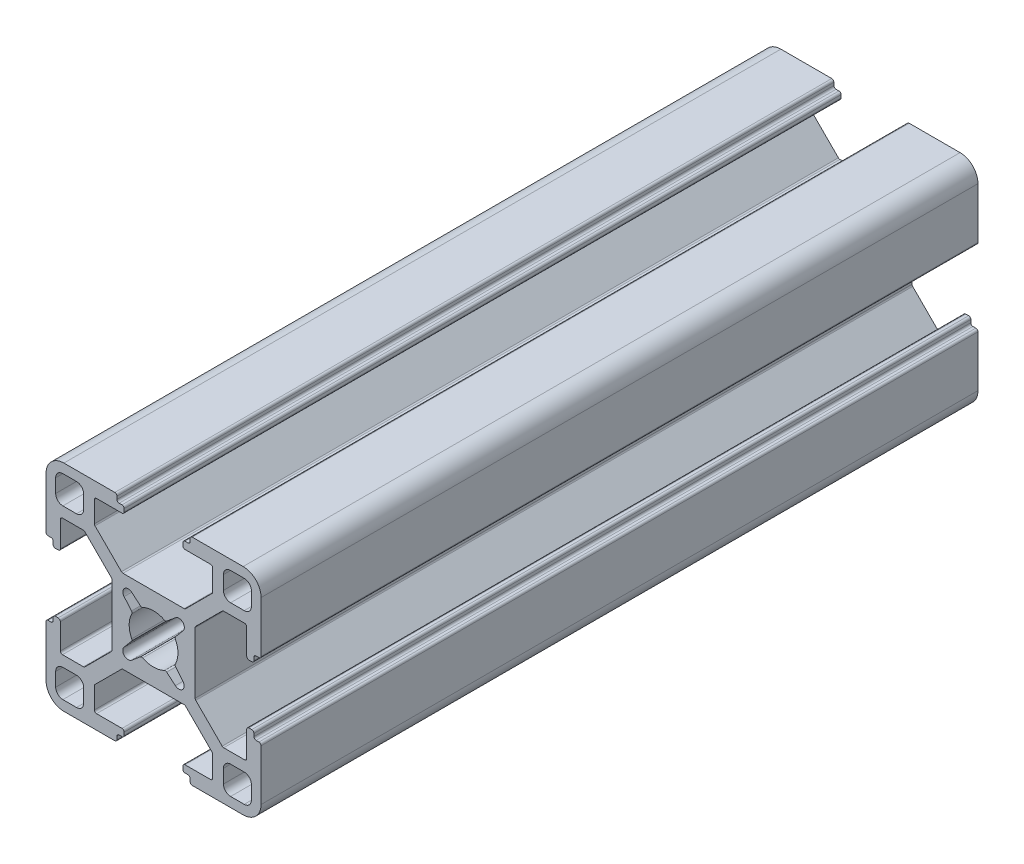
SolidWorks part; units mm, degrees
ref_plane "前视基准面" through (0, 0, 0) normal (0, 0, 1) x (1, 0, 0)
ref_plane "上视基准面" through (0, 0, 0) normal (0, 1, 0) x (1, 0, 0)
ref_plane "右视基准面" through (0, 0, 0) normal (1, 0, 0) x (0, 0, -1)
sketch "草图1" plane through (0, 0, 0) normal (0, 0, 1) x (1, 0, 0)
  line B0 (-13.65, 12.65) -> (-13.65, 10.75)
  line B1 (-12.65, 9.75) -> (-10.75, 9.75)
  line B2 (-9.75, 10.75) -> (-9.75, 12.65)
  line B3 (-10.75, 13.65) -> (-12.65, 13.65)
  line B4 (12.65, 13.65) -> (10.75, 13.65)
  line B5 (9.75, 12.65) -> (9.75, 10.75)
  line B6 (10.75, 9.75) -> (12.65, 9.75)
  line B7 (13.65, 10.75) -> (13.65, 12.65)
  line B8 (-12.65, -13.65) -> (-10.75, -13.65)
  line B9 (-9.75, -12.65) -> (-9.75, -10.75)
  line B10 (-10.75, -9.75) -> (-12.65, -9.75)
  line B11 (-13.65, -10.75) -> (-13.65, -12.65)
  line B12 (9.75, -10.75) -> (9.75, -12.65)
  line B13 (10.75, -13.65) -> (12.65, -13.65)
  line B14 (13.65, -12.65) -> (13.65, -10.75)
  line B15 (12.65, -9.75) -> (10.75, -9.75)
  line B16 (14.3, 5.1) -> (14.7, 5.1)
  line B17 (15, 5.4) -> (15, 12.5)
  line B18 (12.5, 15) -> (5.4, 15)
  line B19 (5.1, 14.7) -> (5.1, 14.3)
  line B20 (4.8, 14) -> (4.4, 14)
  line B21 (4.1, 13.7) -> (4.1, 13.3)
  line B22 (4.4, 13) -> (7.95, 13)
  line B23 (8.25, 12.7) -> (8.25, 9.7885)
  line B24 (8.1621, 9.5763) -> (4.4737, 5.8879)
  line B25 (4.2615, 5.8) -> (0, 5.8)
  line B26 (0, 5.8) -> (-4.2615, 5.8)
  line B27 (-4.4737, 5.8879) -> (-8.1621, 9.5763)
  line B28 (-8.25, 9.7885) -> (-8.25, 12.7)
  line B29 (-7.95, 13) -> (-4.4, 13)
  line B30 (-4.1, 13.3) -> (-4.1, 13.7)
  line B31 (-4.4, 14) -> (-4.8, 14)
  line B32 (-5.1, 14.3) -> (-5.1, 14.7)
  line B33 (-5.4, 15) -> (-12.5, 15)
  line B34 (-15, 12.5) -> (-15, 5.4)
  line B35 (-14.7, 5.1) -> (-14.3, 5.1)
  line B36 (-14, 4.8) -> (-14, 4.4)
  line B37 (-13.7, 4.1) -> (-13.3, 4.1)
  line B38 (-13, 4.4) -> (-13, 7.95)
  line B39 (-12.7, 8.25) -> (-9.7885, 8.25)
  line B40 (-9.5763, 8.1621) -> (-5.8879, 4.4737)
  line B41 (-5.8, 4.2615) -> (-5.8, 0)
  line B42 (-5.8, 0) -> (-5.8, -4.2615)
  line B43 (-5.8879, -4.4737) -> (-9.5763, -8.1621)
  line B44 (-9.7885, -8.25) -> (-12.7, -8.25)
  line B45 (-13, -7.95) -> (-13, -4.4)
  line B46 (-13.3, -4.1) -> (-13.7, -4.1)
  line B47 (-14, -4.4) -> (-14, -4.8)
  line B48 (-14.3, -5.1) -> (-14.7, -5.1)
  line B49 (-15, -5.4) -> (-15, -12.5)
  line B50 (-12.5, -15) -> (-5.4, -15)
  line B51 (-5.1, -14.7) -> (-5.1, -14.3)
  line B52 (-4.8, -14) -> (-4.4, -14)
  line B53 (-4.1, -13.7) -> (-4.1, -13.3)
  line B54 (-4.4, -13) -> (-7.95, -13)
  line B55 (-8.25, -12.7) -> (-8.25, -9.6642)
  line B56 (-8.25, -9.6642) -> (-4.3858, -5.8)
  line B57 (-4.3858, -5.8) -> (0, -5.8)
  line B58 (0, -5.8) -> (4.3858, -5.8)
  line B59 (4.3858, -5.8) -> (8.1621, -9.5763)
  line B60 (8.25, -9.7885) -> (8.25, -12.7)
  line B61 (7.95, -13) -> (4.4, -13)
  line B62 (4.1, -13.3) -> (4.1, -13.7)
  line B63 (4.4, -14) -> (4.8, -14)
  line B64 (5.1, -14.3) -> (5.1, -14.7)
  line B65 (5.4, -15) -> (12.5, -15)
  line B66 (15, -12.5) -> (15, -5.4)
  line B67 (14.7, -5.1) -> (14.3, -5.1)
  line B68 (14, -4.8) -> (14, -4.4)
  line B69 (13.7, -4.1) -> (13.3, -4.1)
  line B70 (13, -4.4) -> (13, -7.95)
  line B71 (12.7, -8.25) -> (9.7885, -8.25)
  line B72 (9.5763, -8.1621) -> (5.8879, -4.4737)
  line B73 (5.8, -4.2615) -> (5.8, 0)
  line B74 (5.8, 0) -> (5.8, 4.2615)
  line B75 (5.8879, 4.4737) -> (9.5763, 8.1621)
  line B76 (9.7885, 8.25) -> (12.7, 8.25)
  line B77 (13, 7.95) -> (13, 4.4)
  line B78 (13.3, 4.1) -> (13.7, 4.1)
  line B79 (14, 4.4) -> (14, 4.8)
  line B80 (-1.83, 3.0889) -> (-3.0493, 4.1167)
  line B81 (-4.103, 3.0678) -> (-3.0807, 1.8439)
  line B82 (-3.0889, -1.83) -> (-4.1167, -3.0493)
  line B83 (-3.0678, -4.103) -> (-1.8439, -3.0807)
  line B84 (1.83, -3.0889) -> (3.0493, -4.1167)
  line B85 (4.103, -3.0678) -> (3.0807, -1.8439)
  line B86 (3.0889, 1.83) -> (4.1167, 3.0493)
  line B87 (3.0678, 4.103) -> (1.8439, 3.0807)
  arc B88 (-13.65, 10.75) -> (-12.65, 9.75) centre (-12.65, 10.75) ccw
  arc B89 (-10.75, 9.75) -> (-9.75, 10.75) centre (-10.75, 10.75) ccw
  arc B90 (-9.75, 12.65) -> (-10.75, 13.65) centre (-10.75, 12.65) ccw
  arc B91 (-12.65, 13.65) -> (-13.65, 12.65) centre (-12.65, 12.65) ccw
  arc B92 (10.75, 13.65) -> (9.75, 12.65) centre (10.75, 12.65) ccw
  arc B93 (9.75, 10.75) -> (10.75, 9.75) centre (10.75, 10.75) ccw
  arc B94 (12.65, 9.75) -> (13.65, 10.75) centre (12.65, 10.75) ccw
  arc B95 (13.65, 12.65) -> (12.65, 13.65) centre (12.65, 12.65) ccw
  arc B96 (-13.65, -12.65) -> (-12.65, -13.65) centre (-12.65, -12.65) ccw
  arc B97 (-10.75, -13.65) -> (-9.75, -12.65) centre (-10.75, -12.65) ccw
  arc B98 (-9.75, -10.75) -> (-10.75, -9.75) centre (-10.75, -10.75) ccw
  arc B99 (-12.65, -9.75) -> (-13.65, -10.75) centre (-12.65, -10.75) ccw
  arc B100 (10.75, -9.75) -> (9.75, -10.75) centre (10.75, -10.75) ccw
  arc B101 (9.75, -12.65) -> (10.75, -13.65) centre (10.75, -12.65) ccw
  arc B102 (12.65, -13.65) -> (13.65, -12.65) centre (12.65, -12.65) ccw
  arc B103 (13.65, -10.75) -> (12.65, -9.75) centre (12.65, -10.75) ccw
  arc B104 (14.7, 5.1) -> (15, 5.4) centre (14.7, 5.4) ccw
  arc B105 (15, 12.5) -> (12.5, 15) centre (12.5, 12.5) ccw
  arc B106 (5.4, 15) -> (5.1, 14.7) centre (5.4, 14.7) ccw
  arc B107 (4.8, 14) -> (5.1, 14.3) centre (4.8, 14.3) ccw
  arc B108 (4.4, 14) -> (4.1, 13.7) centre (4.4, 13.7) ccw
  arc B109 (4.1, 13.3) -> (4.4, 13) centre (4.4, 13.3) ccw
  arc B110 (8.25, 12.7) -> (7.95, 13) centre (7.95, 12.7) ccw
  arc B111 (8.1621, 9.5763) -> (8.25, 9.7885) centre (7.95, 9.7885) ccw
  arc B112 (4.2615, 5.8) -> (4.4737, 5.8879) centre (4.2615, 6.1) ccw
  arc B113 (-4.4737, 5.8879) -> (-4.2615, 5.8) centre (-4.2615, 6.1) ccw
  arc B114 (-8.25, 9.7885) -> (-8.1621, 9.5763) centre (-7.95, 9.7885) ccw
  arc B115 (-7.95, 13) -> (-8.25, 12.7) centre (-7.95, 12.7) ccw
  arc B116 (-4.4, 13) -> (-4.1, 13.3) centre (-4.4, 13.3) ccw
  arc B117 (-4.1, 13.7) -> (-4.4, 14) centre (-4.4, 13.7) ccw
  arc B118 (-5.1, 14.3) -> (-4.8, 14) centre (-4.8, 14.3) ccw
  arc B119 (-5.1, 14.7) -> (-5.4, 15) centre (-5.4, 14.7) ccw
  arc B120 (-12.5, 15) -> (-15, 12.5) centre (-12.5, 12.5) ccw
  arc B121 (-15, 5.4) -> (-14.7, 5.1) centre (-14.7, 5.4) ccw
  arc B122 (-14, 4.8) -> (-14.3, 5.1) centre (-14.3, 4.8) ccw
  arc B123 (-14, 4.4) -> (-13.7, 4.1) centre (-13.7, 4.4) ccw
  arc B124 (-13.3, 4.1) -> (-13, 4.4) centre (-13.3, 4.4) ccw
  arc B125 (-12.7, 8.25) -> (-13, 7.95) centre (-12.7, 7.95) ccw
  arc B126 (-9.5763, 8.1621) -> (-9.7885, 8.25) centre (-9.7885, 7.95) ccw
  arc B127 (-5.8, 4.2615) -> (-5.8879, 4.4737) centre (-6.1, 4.2615) ccw
  arc B128 (-5.8879, -4.4737) -> (-5.8, -4.2615) centre (-6.1, -4.2615) ccw
  arc B129 (-9.7885, -8.25) -> (-9.5763, -8.1621) centre (-9.7885, -7.95) ccw
  arc B130 (-13, -7.95) -> (-12.7, -8.25) centre (-12.7, -7.95) ccw
  arc B131 (-13, -4.4) -> (-13.3, -4.1) centre (-13.3, -4.4) ccw
  arc B132 (-13.7, -4.1) -> (-14, -4.4) centre (-13.7, -4.4) ccw
  arc B133 (-14.3, -5.1) -> (-14, -4.8) centre (-14.3, -4.8) ccw
  arc B134 (-14.7, -5.1) -> (-15, -5.4) centre (-14.7, -5.4) ccw
  arc B135 (-15, -12.5) -> (-12.5, -15) centre (-12.5, -12.5) ccw
  arc B136 (-5.4, -15) -> (-5.1, -14.7) centre (-5.4, -14.7) ccw
  arc B137 (-4.8, -14) -> (-5.1, -14.3) centre (-4.8, -14.3) ccw
  arc B138 (-4.4, -14) -> (-4.1, -13.7) centre (-4.4, -13.7) ccw
  arc B139 (-4.1, -13.3) -> (-4.4, -13) centre (-4.4, -13.3) ccw
  arc B140 (-8.25, -12.7) -> (-7.95, -13) centre (-7.95, -12.7) ccw
  arc B141 (8.25, -9.7885) -> (8.1621, -9.5763) centre (7.95, -9.7885) ccw
  arc B142 (7.95, -13) -> (8.25, -12.7) centre (7.95, -12.7) ccw
  arc B143 (4.4, -13) -> (4.1, -13.3) centre (4.4, -13.3) ccw
  arc B144 (4.1, -13.7) -> (4.4, -14) centre (4.4, -13.7) ccw
  arc B145 (5.1, -14.3) -> (4.8, -14) centre (4.8, -14.3) ccw
  arc B146 (5.1, -14.7) -> (5.4, -15) centre (5.4, -14.7) ccw
  arc B147 (12.5, -15) -> (15, -12.5) centre (12.5, -12.5) ccw
  arc B148 (15, -5.4) -> (14.7, -5.1) centre (14.7, -5.4) ccw
  arc B149 (14, -4.8) -> (14.3, -5.1) centre (14.3, -4.8) ccw
  arc B150 (14, -4.4) -> (13.7, -4.1) centre (13.7, -4.4) ccw
  arc B151 (13.3, -4.1) -> (13, -4.4) centre (13.3, -4.4) ccw
  arc B152 (12.7, -8.25) -> (13, -7.95) centre (12.7, -7.95) ccw
  arc B153 (9.5763, -8.1621) -> (9.7885, -8.25) centre (9.7885, -7.95) ccw
  arc B154 (5.8, -4.2615) -> (5.8879, -4.4737) centre (6.1, -4.2615) ccw
  arc B155 (5.8879, 4.4737) -> (5.8, 4.2615) centre (6.1, 4.2615) ccw
  arc B156 (9.7885, 8.25) -> (9.5763, 8.1621) centre (9.7885, 7.95) ccw
  arc B157 (13, 7.95) -> (12.7, 8.25) centre (12.7, 7.95) ccw
  arc B158 (13, 4.4) -> (13.3, 4.1) centre (13.3, 4.4) ccw
  arc B159 (13.7, 4.1) -> (14, 4.4) centre (13.7, 4.4) ccw
  arc B160 (14.3, 5.1) -> (14, 4.8) centre (14.3, 4.8) ccw
  arc B161 (-3.0493, 4.1167) -> (-4.103, 3.0678) centre (-3.5302, 3.5461) ccw
  arc B162 (-3.0425, 1.5177) -> (-3.0807, 1.8439) centre (-3.3109, 1.6516) ccw
  arc B163 (-3.0425, 1.5177) -> (-3.0493, -1.504) centre (0, 0) ccw
  arc B164 (-3.0889, -1.83) -> (-3.0493, -1.504) centre (-3.3183, -1.6367) ccw
  arc B165 (-4.1167, -3.0493) -> (-3.0678, -4.103) centre (-3.5461, -3.5302) ccw
  arc B166 (-1.5177, -3.0425) -> (-1.8439, -3.0807) centre (-1.6516, -3.3109) ccw
  arc B167 (-1.5177, -3.0425) -> (1.504, -3.0493) centre (0, 0) ccw
  arc B168 (1.83, -3.0889) -> (1.504, -3.0493) centre (1.6367, -3.3183) ccw
  arc B169 (3.0493, -4.1167) -> (4.103, -3.0678) centre (3.5302, -3.5461) ccw
  arc B170 (3.0425, -1.5177) -> (3.0807, -1.8439) centre (3.3109, -1.6516) ccw
  arc B171 (3.0425, -1.5177) -> (3.0493, 1.504) centre (0, 0) ccw
  arc B172 (3.0889, 1.83) -> (3.0493, 1.504) centre (3.3183, 1.6367) ccw
  arc B173 (4.1167, 3.0493) -> (3.0678, 4.103) centre (3.5461, 3.5302) ccw
  arc B174 (1.5177, 3.0425) -> (1.8439, 3.0807) centre (1.6516, 3.3109) ccw
  arc B175 (1.5177, 3.0425) -> (-1.504, 3.0493) centre (0, 0) ccw
  arc B176 (-1.83, 3.0889) -> (-1.504, 3.0493) centre (-1.6367, 3.3183) ccw
sketch_block_instance "A$C722A4DC9-1"
sketch_block "A$C722A4DC9"
extrude "凸台-拉伸1" add sketch "草图1" along normal blind 100
